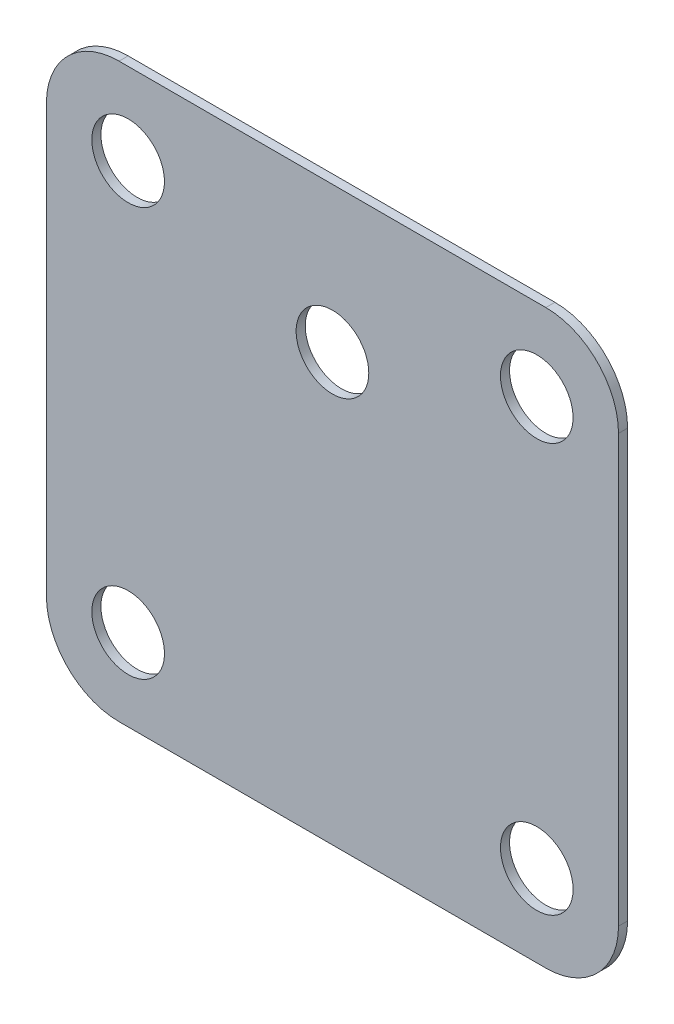
SolidWorks part; units mm, degrees
ref_plane "前视基准面" through (0, 0, 0) normal (0, 0, 1) x (1, 0, 0)
ref_plane "上视基准面" through (0, 0, 0) normal (0, 1, 0) x (1, 0, 0)
ref_plane "右视基准面" through (0, 0, 0) normal (1, 0, 0) x (0, 0, -1)
sketch "草图1" plane through (0, 0, 0) normal (0, 0, 1) x (1, 0, 0)
  line L0 (-48.0889, 0) -> (51.1127, 0) construction
  line L1 (-23.5, 31.5) -> (23.5, 31.5)
  line L2 (-31.5, 23.5) -> (-31.5, -23.5)
  line L3 (-23.5, -31.5) -> (23.5, -31.5)
  line L4 (31.5, 23.5) -> (31.5, -23.5)
  line L5 (-31.5, 31.5) -> (31.5, -31.5) construction
  line L6 (-31.5, -31.5) -> (31.5, 31.5) construction
  line L7 (0, -54.2242) -> (0, 44.3574) construction
  arc A0 (-23.5, 31.5) -> (-31.5, 23.5) centre (-23.5, 23.5) ccw
  arc A1 (-23.5, -31.5) -> (-31.5, -23.5) centre (-23.5, -23.5) cw
  arc A2 (23.5, -31.5) -> (31.5, -23.5) centre (23.5, -23.5) ccw
  arc A3 (31.5, 23.5) -> (23.5, 31.5) centre (23.5, 23.5) ccw
  circle A4 centre (-22.5, 22.5) radius 4
  circle A5 centre (22.5, 22.5) radius 4
  circle A6 centre (22.5, -22.5) radius 4
  circle A7 centre (-22.5, -22.5) radius 4
  circle A8 centre (0, 15.5) radius 4
  point P0 (0, 0)
  dimension "D3" = 8
  dimension "D6" = 8
  dimension "8" = 8
  dimension "D1" = 63
  dimension "D2" = 63
  dimension "D4" = 9
  dimension "D5" = 9
  dimension "D7" = 16
extrude "凸台-拉伸1" add sketch "草图1" along normal blind 1
